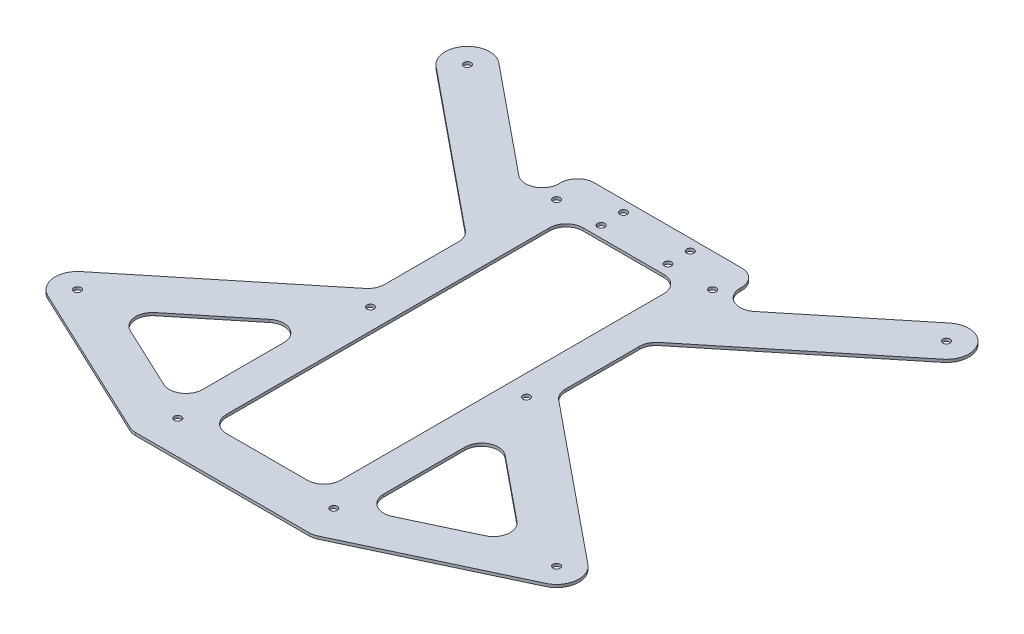
SolidWorks part; units mm, degrees
ref_plane "Front Plane" through (0, 0, 0) normal (0, 0, 1) x (1, 0, 0)
ref_plane "Top Plane" through (0, 0, 0) normal (0, 1, 0) x (1, 0, 0)
ref_plane "Right Plane" through (0, 0, 0) normal (1, 0, 0) x (0, 0, -1)
sketch "Sketch2" plane through (0, 0, 0) normal (0, 1, 0) x (1, 0, 0)
  line L0 (-136.525, 111.125) -> (136.525, -111.125) construction
  line L1 (-128.5079, 120.9746) -> (-51.5937, 58.3701)
  line L2 (-144.5421, 101.2754) -> (-51.5937, 25.6197)
  line L3 (-136.525, -111.125) -> (136.525, 111.125) construction
  line L4 (-144.5421, -101.2754) -> (-51.5937, -25.6197)
  line L5 (-114.9237, -109.9177) -> (-51.5937, -58.3701)
  line L7 (-32.5437, -139.7) -> (32.5437, -139.7)
  line L8 (-32.5437, -139.7) -> (-32.5437, 63.5)
  line L9 (-32.5437, 63.5) -> (32.5437, 63.5)
  line L10 (32.5437, -139.7) -> (32.5437, 63.5)
  line L11 (-32.5437, -139.7) -> (32.5437, 63.5) construction
  line L12 (-32.5437, 63.5) -> (32.5437, -139.7) construction
  line L16 (51.5937, -58.3701) -> (114.9237, -109.9177)
  line L18 (-51.5937, -58.3701) -> (-51.5937, -165.1)
  line L19 (-51.5937, -165.1) -> (51.5937, -165.1)
  line L20 (51.5937, 58.3701) -> (128.5079, 120.9746)
  line L21 (51.5937, 25.6197) -> (144.5421, 101.2754)
  line L22 (51.5937, -25.6197) -> (144.5421, -101.2754)
  line L23 (-51.5937, 58.3701) -> (-51.5937, 88.9)
  line L24 (51.5937, -139.7) -> (51.5937, -58.3701)
  line L25 (51.5937, -25.6197) -> (51.5937, 25.6197)
  line L26 (-51.5937, -25.6197) -> (-51.5937, 25.6197)
  line L27 (-51.5937, 88.9) -> (51.5938, 88.9)
  line L28 (51.5938, 88.9) -> (51.5937, 58.3701)
  line L29 (51.5937, -165.1) -> (141.9296, -122.6176)
  line L30 (114.9237, -109.9177) -> (51.5937, -139.7)
  line L31 (-141.9296, -122.6176) -> (-51.5937, -165.1)
  line L32 (-51.5937, -139.7) -> (-114.9237, -109.9177)
  arc A0 (-128.5079, 120.9746) -> (-144.5421, 101.2754) centre (-136.525, 111.125) ccw
  arc A1 (141.9296, -122.6176) -> (144.5421, -101.2754) centre (136.525, -111.125) ccw
  arc A2 (-144.5421, -101.2754) -> (-141.9296, -122.6176) centre (-136.525, -111.125) ccw
  arc A3 (144.5421, 101.2754) -> (128.5079, 120.9746) centre (136.525, 111.125) ccw
  circle A4 centre (-136.525, 111.125) radius 2.032
  circle A5 centre (136.525, 111.125) radius 2.032
  circle A6 centre (136.525, -111.125) radius 2.032
  circle A7 centre (-136.525, -111.125) radius 2.032
  point P2 (0, 0)
  point P9 (0, 0)
  point P18 (0, -38.1)
  point P39 (0, 0)
  dimension "D3" = 12.7
  dimension "D9" = 4.064
  dimension "D1" = 273.05
  dimension "D2" = 222.25
  dimension "D4" = 65.0875
  dimension "D5" = 63.5
  dimension "D6" = 139.7
  dimension "D8" = 25.4
  dimension "D10" = 19.05
  dimension "D7" = 19.05
  dimension "D11" = 25.4
  dimension "D12" = 22.9852
extrude "Boss-Extrude1" add sketch "Sketch2" along normal mid plane 1.5875
sketch "Sketch3" plane through (0, -0.7937, 0) normal (0, -1, 0) x (1, 0, 0)
  line L0 (-144.5421, 101.2754) -> (-51.5937, 25.6197) construction
  line L1 (-51.5937, -88.9) -> (51.5938, -88.9) construction
  line L2 (44.45, -69.85) -> (51.5938, -69.85) construction
  line L4 (-44.45, -69.85) -> (-51.5937, -69.85) construction
  line L6 (-51.5937, -58.3701) -> (-51.5937, -88.9) construction
  line L7 (51.5938, -88.9) -> (51.5938, -58.3701) construction
  circle A2 centre (44.45, 146.05) radius 2.032
  circle A3 centre (-44.45, 146.05) radius 2.032
  circle A4 centre (44.45, -69.85) radius 2.032
  circle A5 centre (-44.45, -69.85) radius 2.032
  circle A6 centre (-19.05, -69.85) radius 2.032
  circle A7 centre (19.05, -69.85) radius 2.032
  circle A8 centre (-19.05, -82.55) radius 2.032
  circle A9 centre (19.05, -82.55) radius 2.032
  circle A10 centre (-44.45, 36.1802) radius 2.032
  circle A11 centre (44.45, 36.1802) radius 2.032
  point P21 (0, 0)
  point P25 (0, 0)
  point P30 (0, 0)
  point P33 (-19.05, -69.85)
  point P34 (19.05, -69.85)
  point P35 (-19.05, -69.85)
  point P36 (-44.45, -69.85)
  point P37 (0, 0)
  dimension "D3" = 4.064
  dimension "D1" = 25.4
  dimension "D2" = 12.7
  dimension "D4" = 25.4
  dimension "D5" = 88.9
  dimension "D6" = 12.7
  dimension "D7" = 19.05
  dimension "D8" = 12.7
  dimension "D9" = 215.9
extrude "Cut-Extrude1" cut sketch "Sketch3" against normal through all
fillet "Fillet1" radius 9.525 20 edges at (51.5937, 0, 165.1) (-51.5937, 0, 165.1) (-51.5937, 0, -88.9) (51.5938, 0, -88.9) (32.5437, 0, -63.5) (-32.5437, 0, -63.5) (-32.5437, 0, 139.7) (51.5937, 0, 139.7) (32.5437, 0, 139.7) (114.9237, 0, 109.9177) (51.5937, 0, 58.3701) (51.5937, 0, 25.6197) (51.5937, 0, -25.6197) (51.5938, 0, -58.3701) (-51.5937, 0, -58.3701) (-51.5937, 0, -25.6197) (-51.5937, 0, 25.6197) (-51.5937, 0, 139.7) (-114.9237, 0, 109.9177) (-51.5937, 0, 58.3701)
